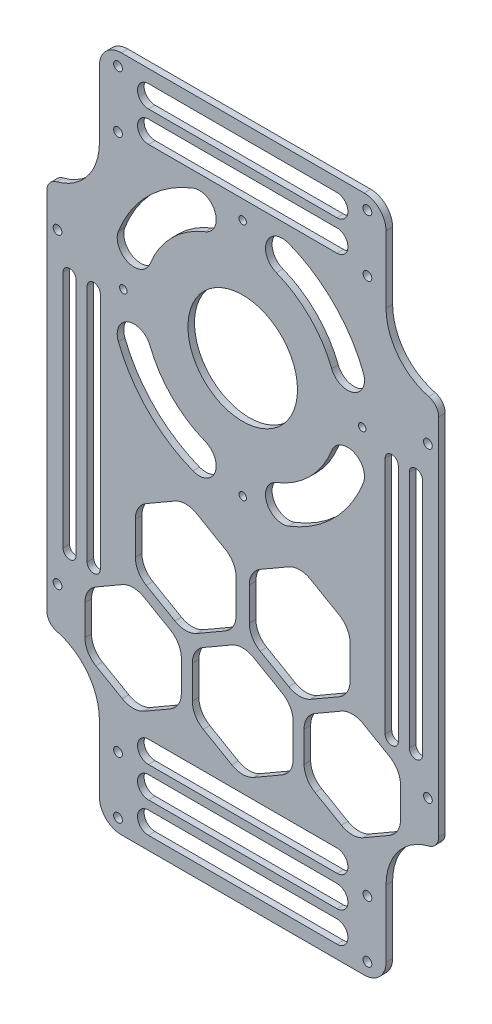
SolidWorks part; units mm, degrees
material "Thornel Mat VMA"
ref_plane "前视基准面" through (0, 0, 0) normal (0, 0, 1) x (1, 0, 0)
ref_plane "上视基准面" through (0, 0, 0) normal (0, 1, 0) x (1, 0, 0)
ref_plane "右视基准面" through (0, 0, 0) normal (1, 0, 0) x (0, 0, -1)
other "Configuration Table"
sketch "草图1" plane through (0, 0, 0) normal (0, 0, 1) x (1, 0, 0)
  line L0 (-16, 16) -> (134.8, 16)
  line L1 (0, 0) -> (118.8, 0)
  line L2 (0, 0) -> (0, -305.05)
  line L3 (0, -305.05) -> (118.8, -305.05)
  line L4 (118.8, 0) -> (118.8, -305.05)
  line L5 (134.8, 16) -> (134.8, -321.05)
  line L6 (-16, -321.05) -> (134.8, -321.05)
  line L7 (-16, 16) -> (-16, -321.05)
  line L8 (59.4, -305.05) -> (59.4, 0) construction
  line L9 (0, -152.525) -> (118.8, -152.525) construction
  line L10 (2.5, 0) -> (2.5, -305.05) construction
  line L11 (116.3, 0) -> (116.3, -305.05) construction
  circle A0 centre (2.5, -4.025) radius 2
  circle A1 centre (2.5, -30.025) radius 2
  circle A2 centre (2.5, -275.025) radius 2
  circle A3 centre (2.5, -301.025) radius 2
  circle A4 centre (116.3, -301.025) radius 2
  circle A5 centre (116.3, -275.025) radius 2
  circle A6 centre (116.3, -30.025) radius 2
  circle A7 centre (116.3, -4.025) radius 2
  dimension "D7" = 4
  dimension "D8" = 26
  dimension "D9" = 4
  dimension "D12" = 297
  dimension "D1" = 118.8
  dimension "D2" = 305.05
  dimension "D4" = 2.5
  dimension "D5" = 2.5
  dimension "D11" = 26
  dimension "D3" = 16
extrude "凸台-拉伸1" add sketch "草图1" along normal blind 3 contours L4 L1 L2 L3 A6 A4 A3 A2 A1 A0 A5 A7 | L0 L7 L6 L5 L1 L4 L3 L2
sketch "草图2" plane through (0, 0, 3) normal (0, 0, 1) x (1, 0, 0)
  line L0 (-30, -152.525) -> (148.8, -152.525) construction
  line L1 (-16, 16) -> (-16, -321.05) construction
  line L3 (-30, -63.525) -> (-30, -241.525)
  line L4 (-30, -63.525) -> (-16, -63.525)
  line L5 (59.4, 16) -> (59.4, -321.05) construction
  line L6 (-16, 16) -> (134.8, 16) construction
  line L7 (-16, -321.05) -> (134.8, -321.05) construction
  line L8 (148.8, -63.525) -> (134.8, -63.525)
  line L9 (148.8, -63.525) -> (148.8, -241.525)
  line L10 (134.8, 16) -> (134.8, -321.05) construction
  line L11 (148.8, -241.525) -> (134.8, -241.525)
  line L12 (-30, -241.525) -> (-16, -241.525)
  line L13 (-16, -63.525) -> (-16, -241.525)
  line L14 (134.8, -241.525) -> (134.8, -63.525)
  point P0 (59.4, -152.525)
  point P5 (134.8, -152.525)
  dimension "D1" = 89
  dimension "D2" = 14
extrude "凸台-拉伸2" add sketch "草图2" against normal blind 3
sketch "草图3" plane through (0, 0, 3) normal (0, 0, 1) x (1, 0, 0)
  line L0 (-30, -152.525) -> (148.8, -152.525) construction
  line L1 (-30, -63.525) -> (-30, -241.525) construction
  line L2 (148.8, -241.525) -> (148.8, -63.525) construction
  line L3 (59.4, 16) -> (59.4, -321.05) construction
  line L4 (-16, 16) -> (134.8, 16) construction
  line L6 (-16, -321.05) -> (134.8, -321.05) construction
  line L8 (-16, -321.05) -> (134.8, -321.05)
  circle A4 centre (59.4, -91) radius 54.5 construction
  circle A5 centre (59.4, -36.5) radius 1.7
  circle A6 centre (113.9, -91) radius 1.7
  circle A7 centre (59.4, -145.5) radius 1.7
  circle A8 centre (4.9, -91) radius 1.7
  dimension "D1" = 109
  dimension "D2" = 3.4
  dimension "D3" = 107
extrude "切除-拉伸1" cut sketch "草图3" against normal blind 67 contours A8 | A7 | A6 | A5
sketch "草图4" plane through (0, 0, 3) normal (0, 0, 1) x (1, 0, 0)
  line L0 (-30, -82.525) -> (148.8, -82.525) construction
  line L1 (-30, -63.525) -> (-30, -241.525) construction
  line L2 (148.8, -241.525) -> (148.8, -63.525) construction
  line L4 (59.4, 16) -> (59.4, -321.05) construction
  line L5 (-30, -152.525) -> (148.8, -152.525) construction
  line L16 (134.8, 16) -> (-16, 16)
  line L17 (-16, 16) -> (-16, -63.525)
  line L18 (-16, -63.525) -> (-30, -63.525)
  line L19 (-30, -63.525) -> (-30, -241.525)
  line L20 (-30, -241.525) -> (-16, -241.525)
  line L21 (-16, -241.525) -> (-16, -321.05)
  line L22 (-16, -321.05) -> (134.8, -321.05)
  line L23 (134.8, -321.05) -> (134.8, -241.525)
  line L24 (134.8, -241.525) -> (148.8, -241.525)
  line L25 (148.8, -241.525) -> (148.8, -63.525)
  line L26 (148.8, -63.525) -> (134.8, -63.525)
  line L27 (134.8, -63.525) -> (134.8, 16)
  line L28 (134.8, 16) -> (-16, 16)
  line L29 (-16, 16) -> (-16, -63.525)
  line L30 (-16, -63.525) -> (-30, -63.525)
  line L31 (-30, -63.525) -> (-30, -241.525)
  line L32 (-30, -241.525) -> (-16, -241.525)
  line L33 (-16, -241.525) -> (-16, -321.05)
  line L34 (-16, -321.05) -> (134.8, -321.05)
  line L35 (134.8, -321.05) -> (134.8, -241.525)
  line L36 (134.8, -241.525) -> (148.8, -241.525)
  line L37 (148.8, -241.525) -> (148.8, -63.525)
  line L38 (148.8, -63.525) -> (134.8, -63.525)
  line L39 (134.8, -63.525) -> (134.8, 16)
  circle A0 centre (143.9, -82.525) radius 2
  circle A1 centre (-25.1, -82.525) radius 2
  circle A2 centre (143.9, -222.525) radius 2
  circle A3 centre (-25.1, -222.525) radius 2
  dimension "D3" = 4
  dimension "D1" = 0
  dimension "D2" = 19
  dimension "D4" = 169
extrude "切除-拉伸2" cut sketch "草图4" against normal blind 67 contours A1 | A3 | A2 | A0
sketch "草图5" plane through (0, 0, 3) normal (0, 0, 1) x (1, 0, 0)
  line L0 (-16, 2) -> (134.8, 2)
  line L1 (-30, -152.525) -> (148.8, -152.525) construction
  line L2 (59.4, 16) -> (59.4, -321.05) construction
  line L3 (124.8, 16) -> (124.8, -321.05)
  line L4 (134.8, -63.525) -> (124.8, -63.525)
  line L5 (-16, -63.525) -> (-6, -63.525)
  line L6 (-6, 16) -> (-6, -321.05)
  line L7 (-16, -241.525) -> (-6, -241.525)
  line L8 (134.8, -241.525) -> (124.8, -241.525)
  line L9 (-16, -307.05) -> (134.8, -307.05)
  line L12 (134.8, 16) -> (-16, 16)
  line L13 (-16, 16) -> (-16, -63.525)
  line L14 (-16, -63.525) -> (-30, -63.525)
  line L15 (-30, -63.525) -> (-30, -241.525)
  line L16 (-30, -241.525) -> (-16, -241.525)
  line L17 (-16, -241.525) -> (-16, -321.05)
  line L18 (-16, -321.05) -> (134.8, -321.05)
  line L19 (134.8, -321.05) -> (134.8, -241.525)
  line L20 (134.8, -241.525) -> (148.8, -241.525)
  line L21 (148.8, -241.525) -> (148.8, -63.525)
  line L22 (148.8, -63.525) -> (134.8, -63.525)
  line L23 (134.8, -63.525) -> (134.8, 16)
  line L24 (134.8, 16) -> (-16, 16)
  line L25 (-16, 16) -> (-16, -63.525)
  line L26 (-16, -63.525) -> (-30, -63.525)
  line L27 (-30, -63.525) -> (-30, -241.525)
  line L28 (-30, -241.525) -> (-16, -241.525)
  line L29 (-16, -241.525) -> (-16, -321.05)
  line L30 (-16, -321.05) -> (134.8, -321.05)
  line L31 (134.8, -321.05) -> (134.8, -241.525)
  line L32 (134.8, -241.525) -> (148.8, -241.525)
  line L33 (148.8, -241.525) -> (148.8, -63.525)
  line L34 (148.8, -63.525) -> (134.8, -63.525)
  line L35 (134.8, -63.525) -> (134.8, 16)
  line M33 (134.8, 16) -> (-16, 16)
  line M34 (-16, 16) -> (-16, -63.525)
  line M38 (-16, -241.525) -> (-16, -321.05)
  line M39 (-16, -321.05) -> (134.8, -321.05)
  line M40 (134.8, -321.05) -> (134.8, -241.525)
  line M44 (134.8, -63.525) -> (134.8, 16)
  dimension "D2" = 14
  dimension "D3" = 10
  dimension "D1" = 0
extrude "切除-拉伸3" cut sketch "草图5" against normal blind 67 contours L6 L0 L3 M33 | L6 L0 M33 M34 | L6 L0 L5 M34 | L3 L0 M33 M44 | L4 L0 L3 M44 | L3 L9 L8 M40 | L9 L3 M39 M40 | L9 L6 L3 M39 | L9 L6 M38 M39 | L9 L6 L7 M38
fillet "圆角1" radius 10 4 edges at (-6, -307.05, 1.5) (124.8, -307.05, 1.5) (124.8, 2, 1.5) (-6, 2, 1.5)
fillet "圆角2" radius 6 4 edges at (148.8, -63.525, 1.5) (148.8, -241.525, 1.5) (-30, -63.525, 1.5) (-30, -241.525, 1.5)
fillet "圆角4" radius 26 4 edges at (-6, -241.525, 1.5) (124.8, -241.525, 1.5) (-6, -63.525, 1.5) (124.8, -63.525, 1.5)
sketch "草图6" plane through (0, 0, 3) normal (0, 0, 1) x (1, 0, 0)
  line L0 (-30, -152.525) -> (148.8, -152.525) construction
  line L1 (59.4, 2) -> (59.4, -307.05) construction
  line L2 (16.4, -296.05) -> (102.4, -296.05) construction
  line L3 (16.4, -291.05) -> (102.4, -291.05)
  line L4 (16.4, -301.05) -> (102.4, -301.05)
  line L5 (16.4, -282.05) -> (102.4, -282.05) construction
  line L6 (16.4, -277.05) -> (102.4, -277.05)
  line L7 (16.4, -287.05) -> (102.4, -287.05)
  line L8 (148.8, -235.525) -> (148.8, -69.525)
  line L9 (124.8, -38.5411) -> (124.8, -8)
  line L10 (114.8, 2) -> (4, 2)
  line L11 (-6, -8) -> (-6, -38.5411)
  line L12 (-30, -69.525) -> (-30, -235.525)
  line L13 (-6, -266.5089) -> (-6, -297.05)
  line L14 (4, -307.05) -> (114.8, -307.05)
  line L15 (124.8, -297.05) -> (124.8, -266.5089)
  line L16 (148.8, -235.525) -> (148.8, -69.525)
  line L17 (124.8, -38.5411) -> (124.8, -8)
  line L18 (114.8, 2) -> (4, 2)
  line L19 (-6, -8) -> (-6, -38.5411)
  line L20 (-30, -69.525) -> (-30, -235.525)
  line L21 (-6, -266.5089) -> (-6, -297.05)
  line L22 (4, -307.05) -> (114.8, -307.05)
  line L23 (124.8, -297.05) -> (124.8, -266.5089)
  line L24 (16.4, -268.05) -> (102.4, -268.05) construction
  line L25 (16.4, -263.05) -> (102.4, -263.05)
  line L26 (16.4, -273.05) -> (102.4, -273.05)
  line L27 (16.4, -9) -> (102.4, -9) construction
  line L28 (16.4, -14) -> (102.4, -14)
  line L29 (16.4, -4) -> (102.4, -4)
  line L30 (16.4, -23) -> (102.4, -23) construction
  line L31 (16.4, -28) -> (102.4, -28)
  line L32 (16.4, -18) -> (102.4, -18)
  arc A0 (16.4, -291.05) -> (16.4, -301.05) centre (16.4, -296.05) ccw
  arc A1 (102.4, -301.05) -> (102.4, -291.05) centre (102.4, -296.05) ccw
  arc A2 (16.4, -277.05) -> (16.4, -287.05) centre (16.4, -282.05) ccw
  arc A3 (102.4, -287.05) -> (102.4, -277.05) centre (102.4, -282.05) ccw
  arc A4 (16.4, -263.05) -> (16.4, -273.05) centre (16.4, -268.05) ccw
  arc A5 (102.4, -273.05) -> (102.4, -263.05) centre (102.4, -268.05) ccw
  arc A6 (16.4, -14) -> (16.4, -4) centre (16.4, -9) cw
  arc A7 (102.4, -4) -> (102.4, -14) centre (102.4, -9) cw
  arc A8 (16.4, -28) -> (16.4, -18) centre (16.4, -23) cw
  arc A9 (102.4, -18) -> (102.4, -28) centre (102.4, -23) cw
  arc A12 (148.8, -69.525) -> (144.3, -63.7155) centre (142.8, -69.525) ccw
  arc A13 (124.8, -38.5411) -> (144.3, -63.7155) centre (150.8, -38.5411) ccw
  arc A14 (124.8, -8) -> (114.8, 2) centre (114.8, -8) ccw
  arc A15 (4, 2) -> (-6, -8) centre (4, -8) ccw
  arc A16 (-25.5, -63.7155) -> (-6, -38.5411) centre (-32, -38.5411) ccw
  arc A17 (-25.5, -63.7155) -> (-30, -69.525) centre (-24, -69.525) ccw
  arc A18 (-30, -235.525) -> (-25.5, -241.3345) centre (-24, -235.525) ccw
  arc A19 (-6, -266.5089) -> (-25.5, -241.3345) centre (-32, -266.5089) ccw
  arc A20 (-6, -297.05) -> (4, -307.05) centre (4, -297.05) ccw
  arc A21 (114.8, -307.05) -> (124.8, -297.05) centre (114.8, -297.05) ccw
  arc A22 (144.3, -241.3345) -> (124.8, -266.5089) centre (150.8, -266.5089) ccw
  arc A23 (144.3, -241.3345) -> (148.8, -235.525) centre (142.8, -235.525) ccw
  arc A24 (148.8, -69.525) -> (144.3, -63.7155) centre (142.8, -69.525) ccw
  arc A25 (124.8, -38.5411) -> (144.3, -63.7155) centre (150.8, -38.5411) ccw
  arc A26 (124.8, -8) -> (114.8, 2) centre (114.8, -8) ccw
  arc A27 (4, 2) -> (-6, -8) centre (4, -8) ccw
  arc A28 (-25.5, -63.7155) -> (-6, -38.5411) centre (-32, -38.5411) ccw
  arc A29 (-25.5, -63.7155) -> (-30, -69.525) centre (-24, -69.525) ccw
  arc A30 (-30, -235.525) -> (-25.5, -241.3345) centre (-24, -235.525) ccw
  arc A31 (-6, -266.5089) -> (-25.5, -241.3345) centre (-32, -266.5089) ccw
  arc A32 (-6, -297.05) -> (4, -307.05) centre (4, -297.05) ccw
  arc A33 (114.8, -307.05) -> (124.8, -297.05) centre (114.8, -297.05) ccw
  arc A34 (144.3, -241.3345) -> (124.8, -266.5089) centre (150.8, -266.5089) ccw
  arc A35 (144.3, -241.3345) -> (148.8, -235.525) centre (142.8, -235.525) ccw
  point P28 (59.4, -296.05)
  point P42 (59.4, -282.05)
  point P50 (59.4, -268.05)
  point P62 (59.4, -9)
  point P69 (59.4, -23)
  dimension "D2" = 6
  dimension "D4" = 5
  dimension "D3" = 86
  dimension "D5" = 4
  dimension "D6" = 4
  dimension "D1" = 0
extrude "切除-拉伸4" cut sketch "草图6" against normal blind 10
sketch "草图7" plane through (0, 0, 3) normal (0, 0, 1) x (1, 0, 0)
  line L0 (-16, -321.05) -> (134.8, -321.05) construction
  line L1 (-16, -321.05) -> (134.8, -321.05)
  line L2 (4.9, -91) -> (113.9, -91) construction
  line L3 (59.4, -36.5) -> (59.4, -145.5) construction
  circle A1 centre (59.4, -36.5) radius 1.7
  circle A2 centre (59.4, -36.5) radius 1.7
  circle A3 centre (4.9, -91) radius 1.7
  circle A4 centre (4.9, -91) radius 1.7
  circle A5 centre (59.4, -145.5) radius 1.7
  circle A6 centre (59.4, -145.5) radius 1.7
  circle A7 centre (113.9, -91) radius 1.7
  circle A8 centre (113.9, -91) radius 1.7
  dimension "D1" = 0
  dimension "D2" = 0
  dimension "D3" = 0
  dimension "D4" = 0
sketch "草图8" plane through (0, 0, 3) normal (0, 0, 1) x (1, 0, 0)
  line L0 (59.4, 2) -> (59.4, -307.05) construction
  line L1 (31.4, -237.4201) -> (31.4, -223.5637)
  line L2 (26.4, -214.9034) -> (14.4, -207.9752)
  line L3 (4.4, -207.9752) -> (-7.6, -214.9034)
  line L4 (-12.6, -223.5637) -> (-12.6, -237.4201)
  line L5 (-7.6, -246.0803) -> (4.4, -253.0085)
  line L6 (14.4, -253.0085) -> (26.4, -246.0803)
  line L7 (82.4, -237.9974) -> (82.4, -222.9863)
  line L8 (148.8, -235.525) -> (148.8, -69.525)
  line L9 (124.8, -38.5411) -> (124.8, -8)
  line L10 (114.8, 2) -> (4, 2)
  line L11 (-6, -8) -> (-6, -38.5411)
  line L12 (-30, -69.525) -> (-30, -235.525)
  line L13 (-6, -266.5089) -> (-6, -297.05)
  line L14 (4, -307.05) -> (114.8, -307.05)
  line L15 (124.8, -297.05) -> (124.8, -266.5089)
  line L16 (148.8, -235.525) -> (148.8, -69.525)
  line L17 (124.8, -38.5411) -> (124.8, -8)
  line L18 (114.8, 2) -> (4, 2)
  line L19 (-6, -8) -> (-6, -38.5411)
  line L20 (-30, -69.525) -> (-30, -235.525)
  line L21 (-6, -266.5089) -> (-6, -297.05)
  line L22 (4, -307.05) -> (114.8, -307.05)
  line L23 (124.8, -297.05) -> (124.8, -266.5089)
  line L24 (77.4, -214.3261) -> (64.4, -206.8205)
  line L25 (54.4, -206.8205) -> (41.4, -214.3261)
  line L26 (36.4, -222.9863) -> (36.4, -237.9974)
  line L27 (41.4, -246.6577) -> (54.4, -254.1632)
  line L28 (64.4, -254.1632) -> (77.4, -246.6577)
  line L29 (126.4, -214.9034) -> (114.4, -207.9752)
  line L30 (104.4, -207.9752) -> (92.4, -214.9034)
  line L31 (87.4, -223.5637) -> (87.4, -237.4201)
  line L32 (92.4, -246.0803) -> (104.4, -253.0085)
  line L33 (114.4, -253.0085) -> (126.4, -246.0803)
  line L34 (131.4, -237.4201) -> (131.4, -223.5637)
  line L35 (16.4, -263.05) -> (102.4, -263.05) construction
  line L36 (114.4, -108.6218) -> (114.4, -196.4282)
  line L37 (56.4, -194.1188) -> (56.4, -179.1077)
  line L38 (51.4, -170.4475) -> (38.4, -162.9419)
  line L39 (28.4, -162.9419) -> (15.4, -170.4475)
  line L40 (10.4, -179.1077) -> (10.4, -194.1188)
  line L41 (15.4, -202.7791) -> (28.4, -210.2846)
  line L42 (38.4, -210.2846) -> (51.4, -202.7791)
  line L43 (108.4, -194.1188) -> (108.4, -179.1077)
  line L44 (103.4, -170.4475) -> (90.4, -162.9419)
  line L45 (80.4, -162.9419) -> (67.4, -170.4475)
  line L46 (62.4, -179.1077) -> (62.4, -194.1188)
  line L47 (67.4, -202.7791) -> (80.4, -210.2846)
  line L48 (90.4, -210.2846) -> (103.4, -202.7791)
  line L49 (119.4, -205.0885) -> (114.9, -202.4904)
  line L50 (119.4, -199.8923) -> (119.4, -105.1577)
  line L51 (-30, -152.525) -> (148.8, -152.525) construction
  line L52 (119.4, -99.9615) -> (114.9, -102.5596)
  line L53 (127.4, -98.025) -> (127.4, -207.025) construction
  line L54 (130.4, -98.025) -> (130.4, -207.025)
  line L55 (124.4, -98.025) -> (124.4, -207.025)
  line L56 (138.4, -98.025) -> (138.4, -207.025) construction
  line L61 (141.4, -98.025) -> (141.4, -207.025)
  line L62 (135.4, -98.025) -> (135.4, -207.025)
  line L63 (4.4, -108.6218) -> (4.4, -196.4282)
  line L64 (-0.6, -205.0885) -> (3.9, -202.4904)
  line L65 (-0.6, -199.8923) -> (-0.6, -105.1577)
  line L66 (-0.6, -99.9615) -> (3.9, -102.5596)
  line L67 (-8.6, -98.025) -> (-8.6, -207.025) construction
  line L68 (-11.6, -98.025) -> (-11.6, -207.025)
  line L69 (-5.6, -98.025) -> (-5.6, -207.025)
  line L70 (-19.6, -98.025) -> (-19.6, -207.025) construction
  line L71 (-22.6, -98.025) -> (-22.6, -207.025)
  line L72 (-16.6, -98.025) -> (-16.6, -207.025)
  circle A0 centre (9.4, -230.4919) radius 22 construction
  circle A1 centre (59.4, -230.4919) radius 23 construction
  circle A2 centre (109.4, -230.4919) radius 22 construction
  circle A3 centre (33.4, -186.6133) radius 23 construction
  circle A4 centre (85.4, -186.6133) radius 23 construction
  arc A5 (130.4, -98.025) -> (124.4, -98.025) centre (127.4, -98.025) ccw
  arc A6 (124.4, -207.025) -> (130.4, -207.025) centre (127.4, -207.025) ccw
  arc A11 (141.4, -98.025) -> (135.4, -98.025) centre (138.4, -98.025) ccw
  arc A12 (148.8, -69.525) -> (144.3, -63.7155) centre (142.8, -69.525) ccw
  arc A13 (124.8, -38.5411) -> (144.3, -63.7155) centre (150.8, -38.5411) ccw
  arc A14 (124.8, -8) -> (114.8, 2) centre (114.8, -8) ccw
  arc A15 (4, 2) -> (-6, -8) centre (4, -8) ccw
  arc A16 (-25.5, -63.7155) -> (-6, -38.5411) centre (-32, -38.5411) ccw
  arc A17 (-25.5, -63.7155) -> (-30, -69.525) centre (-24, -69.525) ccw
  arc A18 (-30, -235.525) -> (-25.5, -241.3345) centre (-24, -235.525) ccw
  arc A19 (-6, -266.5089) -> (-25.5, -241.3345) centre (-32, -266.5089) ccw
  arc A20 (-6, -297.05) -> (4, -307.05) centre (4, -297.05) ccw
  arc A21 (114.8, -307.05) -> (124.8, -297.05) centre (114.8, -297.05) ccw
  arc A22 (144.3, -241.3345) -> (124.8, -266.5089) centre (150.8, -266.5089) ccw
  arc A23 (144.3, -241.3345) -> (148.8, -235.525) centre (142.8, -235.525) ccw
  arc A24 (148.8, -69.525) -> (144.3, -63.7155) centre (142.8, -69.525) ccw
  arc A25 (124.8, -38.5411) -> (144.3, -63.7155) centre (150.8, -38.5411) ccw
  arc A26 (124.8, -8) -> (114.8, 2) centre (114.8, -8) ccw
  arc A27 (4, 2) -> (-6, -8) centre (4, -8) ccw
  arc A28 (-25.5, -63.7155) -> (-6, -38.5411) centre (-32, -38.5411) ccw
  arc A29 (-25.5, -63.7155) -> (-30, -69.525) centre (-24, -69.525) ccw
  arc A30 (-30, -235.525) -> (-25.5, -241.3345) centre (-24, -235.525) ccw
  arc A31 (-6, -266.5089) -> (-25.5, -241.3345) centre (-32, -266.5089) ccw
  arc A32 (-6, -297.05) -> (4, -307.05) centre (4, -297.05) ccw
  arc A33 (114.8, -307.05) -> (124.8, -297.05) centre (114.8, -297.05) ccw
  arc A34 (144.3, -241.3345) -> (124.8, -266.5089) centre (150.8, -266.5089) ccw
  arc A35 (144.3, -241.3345) -> (148.8, -235.525) centre (142.8, -235.525) ccw
  arc A36 (135.4, -207.025) -> (141.4, -207.025) centre (138.4, -207.025) ccw
  arc A37 (-11.6, -98.025) -> (-5.6, -98.025) centre (-8.6, -98.025) cw
  arc A38 (-5.6, -207.025) -> (-11.6, -207.025) centre (-8.6, -207.025) cw
  arc A39 (-22.6, -98.025) -> (-16.6, -98.025) centre (-19.6, -98.025) cw
  arc A40 (-16.6, -207.025) -> (-22.6, -207.025) centre (-19.6, -207.025) cw
  arc A41 (56.4, -194.1188) -> (51.4, -202.7791) centre (46.4, -194.1188) cw
  arc A42 (28.4, -210.2846) -> (38.4, -210.2846) centre (33.4, -201.6244) ccw
  arc A43 (10.4, -194.1188) -> (15.4, -202.7791) centre (20.4, -194.1188) ccw
  arc A44 (15.4, -170.4475) -> (10.4, -179.1077) centre (20.4, -179.1077) ccw
  arc A45 (38.4, -162.9419) -> (28.4, -162.9419) centre (33.4, -171.6022) ccw
  arc A46 (56.4, -179.1077) -> (51.4, -170.4475) centre (46.4, -179.1077) ccw
  arc A47 (108.4, -194.1188) -> (103.4, -202.7791) centre (98.4, -194.1188) cw
  arc A48 (108.4, -179.1077) -> (103.4, -170.4475) centre (98.4, -179.1077) ccw
  arc A49 (90.4, -162.9419) -> (80.4, -162.9419) centre (85.4, -171.6022) ccw
  arc A50 (67.4, -170.4475) -> (62.4, -179.1077) centre (72.4, -179.1077) ccw
  arc A51 (62.4, -194.1188) -> (67.4, -202.7791) centre (72.4, -194.1188) ccw
  arc A52 (80.4, -210.2846) -> (90.4, -210.2846) centre (85.4, -201.6244) ccw
  arc A53 (114.4, -207.9752) -> (104.4, -207.9752) centre (109.4, -216.6355) ccw
  arc A54 (126.4, -214.9034) -> (131.4, -223.5637) centre (121.4, -223.5637) cw
  arc A55 (126.4, -246.0803) -> (131.4, -237.4201) centre (121.4, -237.4201) ccw
  arc A56 (104.4, -253.0085) -> (114.4, -253.0085) centre (109.4, -244.3483) ccw
  arc A57 (87.4, -237.4201) -> (92.4, -246.0803) centre (97.4, -237.4201) ccw
  arc A58 (92.4, -214.9034) -> (87.4, -223.5637) centre (97.4, -223.5637) ccw
  arc A59 (64.4, -206.8205) -> (54.4, -206.8205) centre (59.4, -215.4808) ccw
  arc A60 (82.4, -222.9863) -> (77.4, -214.3261) centre (72.4, -222.9863) ccw
  arc A61 (82.4, -237.9974) -> (77.4, -246.6577) centre (72.4, -237.9974) cw
  arc A62 (54.4, -254.1632) -> (64.4, -254.1632) centre (59.4, -245.503) ccw
  arc A63 (36.4, -237.9974) -> (41.4, -246.6577) centre (46.4, -237.9974) ccw
  arc A64 (31.4, -223.5637) -> (26.4, -214.9034) centre (21.4, -223.5637) ccw
  arc A65 (31.4, -237.4201) -> (26.4, -246.0803) centre (21.4, -237.4201) cw
  arc A66 (4.4, -253.0085) -> (14.4, -253.0085) centre (9.4, -244.3483) ccw
  arc A67 (-12.6, -237.4201) -> (-7.6, -246.0803) centre (-2.6, -237.4201) ccw
  arc A68 (-7.6, -214.9034) -> (-12.6, -223.5637) centre (-2.6, -223.5637) ccw
  arc A69 (14.4, -207.9752) -> (4.4, -207.9752) centre (9.4, -216.6355) ccw
  arc A70 (114.4, -196.4282) -> (119.4, -205.0885) centre (124.4, -196.4282) ccw
  arc A71 (114.4, -108.6218) -> (119.4, -99.9615) centre (124.4, -108.6218) cw
  arc A72 (4.4, -196.4282) -> (-0.6, -205.0885) centre (-5.6, -196.4282) cw
  arc A73 (4.4, -108.6218) -> (-0.6, -99.9615) centre (-5.6, -108.6218) ccw
  arc A74 (119.4, -105.1577) -> (114.9, -102.5596) centre (116.4, -105.1577) ccw
  arc A75 (114.9, -202.4904) -> (119.4, -199.8923) centre (116.4, -199.8923) ccw
  arc A76 (3.9, -202.4904) -> (-0.6, -199.8923) centre (2.4, -199.8923) cw
  arc A77 (-0.6, -105.1577) -> (3.9, -102.5596) centre (2.4, -105.1577) cw
  arc A78 (41.4, -214.3261) -> (36.4, -222.9863) centre (46.4, -222.9863) ccw
  point P84 (127.4, -152.525)
  point P91 (138.4, -152.525)
  point P104 (-8.6, -152.525)
  point P111 (-19.6, -152.525)
  point P160 (59.4, -257.05)
  point P177 (114.4, -202.2017)
  point P180 (114.4, -102.8483)
  point P183 (4.4, -202.2017)
  point P186 (4.4, -102.8483)
  point P189 (119.4, -99.9615)
  point P192 (119.4, -205.0885)
  point P195 (-0.6, -205.0885)
  point P198 (-0.6, -99.9615)
  dimension "D8" = 5
  dimension "D18" = 3
  dimension "D20" = 3
  dimension "D22" = 10
  dimension "D23" = 10
  dimension "D24" = 3
  dimension "D25" = 10
  dimension "D2" = 46
  dimension "D3" = 6
  dimension "D4" = 44
  dimension "D5" = 5
  dimension "D6" = 44
  dimension "D7" = 5
  dimension "D9" = 5
  dimension "D10" = 46
  dimension "D11" = 5
  dimension "D12" = 46
  dimension "D13" = 5
  dimension "D14" = 5
  dimension "D15" = 6
  dimension "D16" = 5
  dimension "D17" = 5
  dimension "D19" = 109
  dimension "D21" = 5
  dimension "D1" = 0
extrude "切除-拉伸5" cut sketch "草图8" against normal blind 10 contours A76 L65 A77 L66 A73 L63 A72 L64 | L68 A38 L69 A37 | L71 A40 L72 A39 | L37 A46 L38 A45 L39 A44 L40 A43 L41 A42 L42 A41 | L43 A48 L44 A49 L45 A50 L46 A51 L47 A52 L48 A47 | A58 L31 A57 L32 A56 L33 A55 L34 A54 L29 A53 L30 | A78 L26 A63 L27 A62 L28 A61 L7 A60 L24 A59 L25 | L1 A64 L2 A69 L3 A68 L4 A67 L5 A66 L6 A65 | L52 A74 L50 A75 L49 A70 L36 A71 | L55 A6 L54 A5 | L62 A36 L61 A11
sketch "草图9" plane through (0, 0, 3) normal (0, 0, 1) x (1, 0, 0)
  line L0 (3.2, -91) -> (113.9, -91) construction
  line L2 (141.4, -207.025) -> (141.4, -98.025)
  line L3 (135.4, -98.025) -> (135.4, -207.025)
  line L4 (141.4, -207.025) -> (141.4, -98.025)
  line L5 (135.4, -98.025) -> (135.4, -207.025)
  line L6 (130.4, -207.025) -> (130.4, -98.025)
  line L7 (124.4, -98.025) -> (124.4, -207.025)
  line L8 (-6, -266.5089) -> (-6, -297.05)
  line L9 (4, -307.05) -> (114.8, -307.05)
  line L10 (124.8, -297.05) -> (124.8, -266.5089)
  line L11 (148.8, -235.525) -> (148.8, -69.525)
  line L12 (124.8, -38.5411) -> (124.8, -8)
  line L13 (114.8, 2) -> (4, 2)
  line L14 (-6, -8) -> (-6, -38.5411)
  line L15 (-30, -69.525) -> (-30, -235.525)
  line L16 (-6, -266.5089) -> (-6, -297.05)
  line L17 (4, -307.05) -> (114.8, -307.05)
  line L18 (124.8, -297.05) -> (124.8, -266.5089)
  line L19 (148.8, -235.525) -> (148.8, -69.525)
  line L20 (124.8, -38.5411) -> (124.8, -8)
  line L21 (114.8, 2) -> (4, 2)
  line L22 (-6, -8) -> (-6, -38.5411)
  line L23 (-30, -69.525) -> (-30, -235.525)
  line L24 (130.4, -207.025) -> (130.4, -98.025)
  line L25 (124.4, -98.025) -> (124.4, -207.025)
  line L26 (-11.6, -98.025) -> (-11.6, -207.025)
  line L27 (-5.6, -207.025) -> (-5.6, -98.025)
  line L28 (-11.6, -98.025) -> (-11.6, -207.025)
  line L29 (-5.6, -207.025) -> (-5.6, -98.025)
  line L30 (-22.6, -98.025) -> (-22.6, -207.025)
  line L31 (-16.6, -207.025) -> (-16.6, -98.025)
  line L32 (-22.6, -98.025) -> (-22.6, -207.025)
  line L33 (-16.6, -207.025) -> (-16.6, -98.025)
  line L35 (58.55, -91) -> (16.1236, -48.5736) construction
  line L38 (56.4, -194.1188) -> (56.4, -179.1077)
  line L39 (51.4, -170.4475) -> (38.4, -162.9419)
  line L40 (28.4, -162.9419) -> (15.4, -170.4475)
  line L41 (10.4, -179.1077) -> (10.4, -194.1188)
  line L42 (15.4, -202.7791) -> (28.4, -210.2846)
  line L43 (38.4, -210.2846) -> (51.4, -202.7791)
  line L44 (56.4, -194.1188) -> (56.4, -179.1077)
  line L45 (51.4, -170.4475) -> (38.4, -162.9419)
  line L46 (28.4, -162.9419) -> (15.4, -170.4475)
  line L47 (10.4, -179.1077) -> (10.4, -194.1188)
  line L48 (15.4, -202.7791) -> (28.4, -210.2846)
  line L49 (38.4, -210.2846) -> (51.4, -202.7791)
  line L50 (108.4, -194.1188) -> (108.4, -179.1077)
  line L51 (103.4, -170.4475) -> (90.4, -162.9419)
  line L52 (80.4, -162.9419) -> (67.4, -170.4475)
  line L53 (62.4, -179.1077) -> (62.4, -194.1188)
  line L54 (67.4, -202.7791) -> (80.4, -210.2846)
  line L55 (90.4, -210.2846) -> (103.4, -202.7791)
  line L56 (108.4, -194.1188) -> (108.4, -179.1077)
  line L57 (103.4, -170.4475) -> (90.4, -162.9419)
  line L58 (80.4, -162.9419) -> (67.4, -170.4475)
  line L59 (62.4, -179.1077) -> (62.4, -194.1188)
  line L60 (67.4, -202.7791) -> (80.4, -210.2846)
  line L61 (90.4, -210.2846) -> (103.4, -202.7791)
  line L62 (104.4, -207.9752) -> (92.4, -214.9034)
  line L63 (126.4, -214.9034) -> (114.4, -207.9752)
  line L64 (131.4, -237.4201) -> (131.4, -223.5637)
  line L65 (114.4, -253.0085) -> (126.4, -246.0803)
  line L66 (92.4, -246.0803) -> (104.4, -253.0085)
  line L67 (87.4, -223.5637) -> (87.4, -237.4201)
  line L68 (104.4, -207.9752) -> (92.4, -214.9034)
  line L69 (126.4, -214.9034) -> (114.4, -207.9752)
  line L70 (131.4, -237.4201) -> (131.4, -223.5637)
  line L71 (114.4, -253.0085) -> (126.4, -246.0803)
  line L72 (92.4, -246.0803) -> (104.4, -253.0085)
  line L73 (87.4, -223.5637) -> (87.4, -237.4201)
  line L74 (31.4, -237.4201) -> (31.4, -223.5637)
  line L75 (26.4, -214.9034) -> (14.4, -207.9752)
  line L76 (4.4, -207.9752) -> (-7.6, -214.9034)
  line L77 (-12.6, -223.5637) -> (-12.6, -237.4201)
  line L78 (-7.6, -246.0803) -> (4.4, -253.0085)
  line L79 (14.4, -253.0085) -> (26.4, -246.0803)
  line L80 (31.4, -237.4201) -> (31.4, -223.5637)
  line L81 (26.4, -214.9034) -> (14.4, -207.9752)
  line L82 (4.4, -207.9752) -> (-7.6, -214.9034)
  line L83 (-12.6, -223.5637) -> (-12.6, -237.4201)
  line L84 (-7.6, -246.0803) -> (4.4, -253.0085)
  line L85 (14.4, -253.0085) -> (26.4, -246.0803)
  line L102 (54.4, -206.8205) -> (41.4, -214.3261)
  line L103 (77.4, -214.3261) -> (64.4, -206.8205)
  line L104 (82.4, -237.9974) -> (82.4, -222.9863)
  line L105 (64.4, -254.1632) -> (77.4, -246.6577)
  line L106 (41.4, -246.6577) -> (54.4, -254.1632)
  line L107 (36.4, -222.9863) -> (36.4, -237.9974)
  line L108 (54.4, -206.8205) -> (41.4, -214.3261)
  line L109 (77.4, -214.3261) -> (64.4, -206.8205)
  line L110 (82.4, -237.9974) -> (82.4, -222.9863)
  line L111 (64.4, -254.1632) -> (77.4, -246.6577)
  line L112 (41.4, -246.6577) -> (54.4, -254.1632)
  line L113 (36.4, -222.9863) -> (36.4, -237.9974)
  line L114 (58.55, -91) -> (58.55, -31) construction
  arc A2 (135.4, -207.025) -> (141.4, -207.025) centre (138.4, -207.025) ccw
  arc A3 (141.4, -98.025) -> (135.4, -98.025) centre (138.4, -98.025) ccw
  arc A4 (135.4, -207.025) -> (141.4, -207.025) centre (138.4, -207.025) ccw
  arc A5 (141.4, -98.025) -> (135.4, -98.025) centre (138.4, -98.025) ccw
  arc A6 (124.4, -207.025) -> (130.4, -207.025) centre (127.4, -207.025) ccw
  arc A7 (130.4, -98.025) -> (124.4, -98.025) centre (127.4, -98.025) ccw
  arc A8 (124.4, -207.025) -> (130.4, -207.025) centre (127.4, -207.025) ccw
  arc A9 (130.4, -98.025) -> (124.4, -98.025) centre (127.4, -98.025) ccw
  arc A10 (-11.6, -207.025) -> (-5.6, -207.025) centre (-8.6, -207.025) ccw
  arc A11 (-5.6, -98.025) -> (-11.6, -98.025) centre (-8.6, -98.025) ccw
  arc A12 (-6, -297.05) -> (4, -307.05) centre (4, -297.05) ccw
  arc A13 (114.8, -307.05) -> (124.8, -297.05) centre (114.8, -297.05) ccw
  arc A14 (144.3, -241.3345) -> (124.8, -266.5089) centre (150.8, -266.5089) ccw
  arc A15 (144.3, -241.3345) -> (148.8, -235.525) centre (142.8, -235.525) ccw
  arc A16 (148.8, -69.525) -> (144.3, -63.7155) centre (142.8, -69.525) ccw
  arc A17 (124.8, -38.5411) -> (144.3, -63.7155) centre (150.8, -38.5411) ccw
  arc A18 (124.8, -8) -> (114.8, 2) centre (114.8, -8) ccw
  arc A19 (4, 2) -> (-6, -8) centre (4, -8) ccw
  arc A20 (-25.5, -63.7155) -> (-6, -38.5411) centre (-32, -38.5411) ccw
  arc A21 (-25.5, -63.7155) -> (-30, -69.525) centre (-24, -69.525) ccw
  arc A22 (-30, -235.525) -> (-25.5, -241.3345) centre (-24, -235.525) ccw
  arc A23 (-6, -266.5089) -> (-25.5, -241.3345) centre (-32, -266.5089) ccw
  arc A24 (-6, -297.05) -> (4, -307.05) centre (4, -297.05) ccw
  arc A25 (114.8, -307.05) -> (124.8, -297.05) centre (114.8, -297.05) ccw
  arc A26 (144.3, -241.3345) -> (124.8, -266.5089) centre (150.8, -266.5089) ccw
  arc A27 (144.3, -241.3345) -> (148.8, -235.525) centre (142.8, -235.525) ccw
  arc A28 (148.8, -69.525) -> (144.3, -63.7155) centre (142.8, -69.525) ccw
  arc A29 (124.8, -38.5411) -> (144.3, -63.7155) centre (150.8, -38.5411) ccw
  arc A30 (124.8, -8) -> (114.8, 2) centre (114.8, -8) ccw
  arc A31 (4, 2) -> (-6, -8) centre (4, -8) ccw
  arc A32 (-25.5, -63.7155) -> (-6, -38.5411) centre (-32, -38.5411) ccw
  arc A33 (-25.5, -63.7155) -> (-30, -69.525) centre (-24, -69.525) ccw
  arc A34 (-30, -235.525) -> (-25.5, -241.3345) centre (-24, -235.525) ccw
  arc A35 (-6, -266.5089) -> (-25.5, -241.3345) centre (-32, -266.5089) ccw
  arc A36 (-11.6, -207.025) -> (-5.6, -207.025) centre (-8.6, -207.025) ccw
  arc A37 (-5.6, -98.025) -> (-11.6, -98.025) centre (-8.6, -98.025) ccw
  arc A38 (-22.6, -207.025) -> (-16.6, -207.025) centre (-19.6, -207.025) ccw
  arc A39 (-16.6, -98.025) -> (-22.6, -98.025) centre (-19.6, -98.025) ccw
  arc A40 (-22.6, -207.025) -> (-16.6, -207.025) centre (-19.6, -207.025) ccw
  arc A41 (-16.6, -98.025) -> (-22.6, -98.025) centre (-19.6, -98.025) ccw
  arc A46 (56.4, -179.1077) -> (51.4, -170.4475) centre (46.4, -179.1077) ccw
  arc A47 (38.4, -162.9419) -> (28.4, -162.9419) centre (33.4, -171.6022) ccw
  arc A48 (15.4, -170.4475) -> (10.4, -179.1077) centre (20.4, -179.1077) ccw
  arc A49 (10.4, -194.1188) -> (15.4, -202.7791) centre (20.4, -194.1188) ccw
  arc A50 (28.4, -210.2846) -> (38.4, -210.2846) centre (33.4, -201.6244) ccw
  arc A51 (51.4, -202.7791) -> (56.4, -194.1188) centre (46.4, -194.1188) ccw
  arc A52 (56.4, -179.1077) -> (51.4, -170.4475) centre (46.4, -179.1077) ccw
  arc A53 (38.4, -162.9419) -> (28.4, -162.9419) centre (33.4, -171.6022) ccw
  arc A54 (15.4, -170.4475) -> (10.4, -179.1077) centre (20.4, -179.1077) ccw
  arc A55 (10.4, -194.1188) -> (15.4, -202.7791) centre (20.4, -194.1188) ccw
  arc A56 (28.4, -210.2846) -> (38.4, -210.2846) centre (33.4, -201.6244) ccw
  arc A57 (51.4, -202.7791) -> (56.4, -194.1188) centre (46.4, -194.1188) ccw
  arc A58 (108.4, -179.1077) -> (103.4, -170.4475) centre (98.4, -179.1077) ccw
  arc A59 (90.4, -162.9419) -> (80.4, -162.9419) centre (85.4, -171.6022) ccw
  arc A60 (67.4, -170.4475) -> (62.4, -179.1077) centre (72.4, -179.1077) ccw
  arc A61 (62.4, -194.1188) -> (67.4, -202.7791) centre (72.4, -194.1188) ccw
  arc A62 (80.4, -210.2846) -> (90.4, -210.2846) centre (85.4, -201.6244) ccw
  arc A63 (103.4, -202.7791) -> (108.4, -194.1188) centre (98.4, -194.1188) ccw
  arc A64 (108.4, -179.1077) -> (103.4, -170.4475) centre (98.4, -179.1077) ccw
  arc A65 (90.4, -162.9419) -> (80.4, -162.9419) centre (85.4, -171.6022) ccw
  arc A66 (67.4, -170.4475) -> (62.4, -179.1077) centre (72.4, -179.1077) ccw
  arc A67 (62.4, -194.1188) -> (67.4, -202.7791) centre (72.4, -194.1188) ccw
  arc A68 (80.4, -210.2846) -> (90.4, -210.2846) centre (85.4, -201.6244) ccw
  arc A69 (103.4, -202.7791) -> (108.4, -194.1188) centre (98.4, -194.1188) ccw
  arc A70 (114.4, -207.9752) -> (104.4, -207.9752) centre (109.4, -216.6355) ccw
  arc A71 (131.4, -223.5637) -> (126.4, -214.9034) centre (121.4, -223.5637) ccw
  arc A72 (126.4, -246.0803) -> (131.4, -237.4201) centre (121.4, -237.4201) ccw
  arc A73 (104.4, -253.0085) -> (114.4, -253.0085) centre (109.4, -244.3483) ccw
  arc A74 (87.4, -237.4201) -> (92.4, -246.0803) centre (97.4, -237.4201) ccw
  arc A75 (92.4, -214.9034) -> (87.4, -223.5637) centre (97.4, -223.5637) ccw
  arc A76 (114.4, -207.9752) -> (104.4, -207.9752) centre (109.4, -216.6355) ccw
  arc A77 (131.4, -223.5637) -> (126.4, -214.9034) centre (121.4, -223.5637) ccw
  arc A78 (126.4, -246.0803) -> (131.4, -237.4201) centre (121.4, -237.4201) ccw
  arc A79 (104.4, -253.0085) -> (114.4, -253.0085) centre (109.4, -244.3483) ccw
  arc A80 (87.4, -237.4201) -> (92.4, -246.0803) centre (97.4, -237.4201) ccw
  arc A81 (92.4, -214.9034) -> (87.4, -223.5637) centre (97.4, -223.5637) ccw
  arc A82 (31.4, -223.5637) -> (26.4, -214.9034) centre (21.4, -223.5637) ccw
  arc A83 (14.4, -207.9752) -> (4.4, -207.9752) centre (9.4, -216.6355) ccw
  arc A84 (-7.6, -214.9034) -> (-12.6, -223.5637) centre (-2.6, -223.5637) ccw
  arc A85 (-12.6, -237.4201) -> (-7.6, -246.0803) centre (-2.6, -237.4201) ccw
  arc A86 (4.4, -253.0085) -> (14.4, -253.0085) centre (9.4, -244.3483) ccw
  arc A87 (26.4, -246.0803) -> (31.4, -237.4201) centre (21.4, -237.4201) ccw
  arc A88 (31.4, -223.5637) -> (26.4, -214.9034) centre (21.4, -223.5637) ccw
  arc A89 (14.4, -207.9752) -> (4.4, -207.9752) centre (9.4, -216.6355) ccw
  arc A90 (-7.6, -214.9034) -> (-12.6, -223.5637) centre (-2.6, -223.5637) ccw
  arc A91 (-12.6, -237.4201) -> (-7.6, -246.0803) centre (-2.6, -237.4201) ccw
  arc A92 (4.4, -253.0085) -> (14.4, -253.0085) centre (9.4, -244.3483) ccw
  arc A93 (26.4, -246.0803) -> (31.4, -237.4201) centre (21.4, -237.4201) ccw
  circle A109 centre (4.9, -91) radius 1.7 construction
  arc A110 (64.4, -206.8205) -> (54.4, -206.8205) centre (59.4, -215.4808) ccw
  arc A111 (82.4, -222.9863) -> (77.4, -214.3261) centre (72.4, -222.9863) ccw
  arc A112 (77.4, -246.6577) -> (82.4, -237.9974) centre (72.4, -237.9974) ccw
  arc A113 (54.4, -254.1632) -> (64.4, -254.1632) centre (59.4, -245.503) ccw
  arc A114 (36.4, -237.9974) -> (41.4, -246.6577) centre (46.4, -237.9974) ccw
  arc A115 (41.4, -214.3261) -> (36.4, -222.9863) centre (46.4, -222.9863) ccw
  arc A116 (64.4, -206.8205) -> (54.4, -206.8205) centre (59.4, -215.4808) ccw
  arc A117 (82.4, -222.9863) -> (77.4, -214.3261) centre (72.4, -222.9863) ccw
  arc A118 (77.4, -246.6577) -> (82.4, -237.9974) centre (72.4, -237.9974) ccw
  arc A119 (54.4, -254.1632) -> (64.4, -254.1632) centre (59.4, -245.503) ccw
  arc A120 (36.4, -237.9974) -> (41.4, -246.6577) centre (46.4, -237.9974) ccw
  arc A121 (41.4, -214.3261) -> (36.4, -222.9863) centre (46.4, -222.9863) ccw
  circle A122 centre (58.55, -91) radius 44.5
  circle A123 centre (58.55, -91) radius 60
  circle A124 centre (9.877, -72) radius 7.75
  circle A125 centre (39.55, -42.327) radius 7.75
  circle A126 centre (9.877, -110) radius 7.75
  circle A127 centre (39.55, -139.673) radius 7.75
  circle A128 centre (77.55, -139.673) radius 7.75
  circle A129 centre (107.223, -110) radius 7.75
  circle A130 centre (77.55, -42.327) radius 7.75
  circle A131 centre (107.223, -72) radius 7.75
  dimension "D13" = 89
  dimension "D14" = 120
  dimension "D15" = 19
  dimension "D16" = 45
  dimension "D1" = 0
  dimension "D2" = 0
  dimension "D3" = 0
  dimension "D4" = 0
  dimension "D5" = 0
  dimension "D6" = 0
  dimension "D7" = 0
  dimension "D8" = 0
  dimension "D9" = 0
  dimension "D12" = 0
sketch "草图10" plane through (0, 0, 3) normal (0, 0, 1) x (1, 0, 0)
  line L0 (4.9, -91) -> (113.9, -91) construction
  circle A0 centre (59.4, -91) radius 25
  dimension "D1" = 50
extrude "切除-拉伸8" cut sketch "草图10" against normal blind 10 contours A0
extrude "切除-拉伸9" cut sketch "草图9" against normal blind 10 contours A125 A123 A124 A122 | A125 | A124 | A122 A131 A123 A130 | A130 | A131 | A129 A122 A128 A123 | A129 | A128 | A127 | A123 A127 A122 A126 | A126
